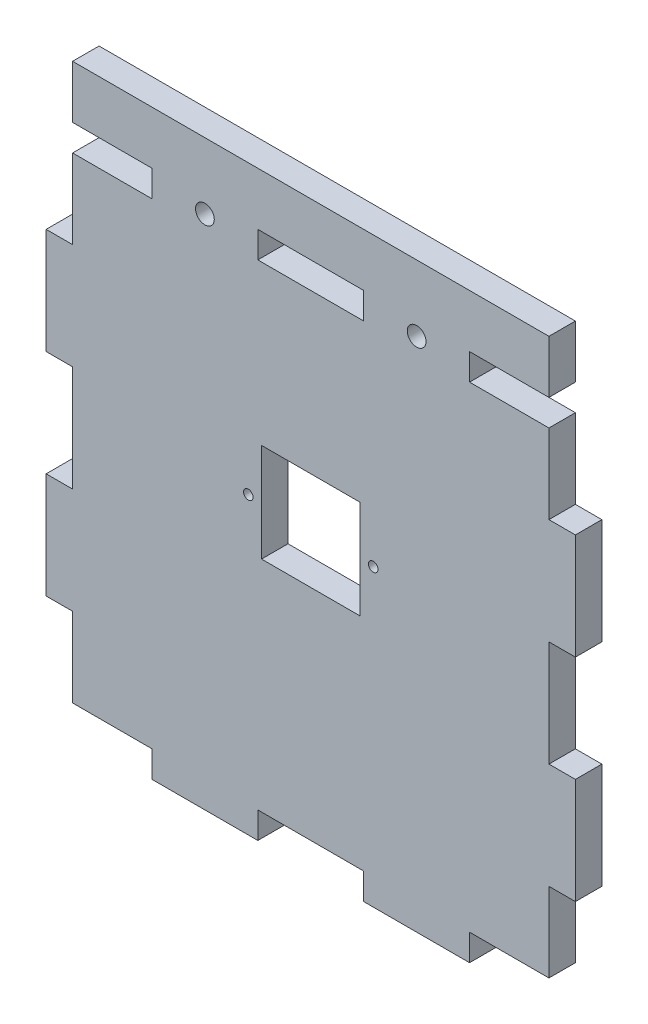
SolidWorks part; units mm, degrees
ref_plane "Front Plane" through (0, 0, 0) normal (0, 0, 1) x (1, 0, 0)
ref_plane "Top Plane" through (0, 0, 0) normal (0, 1, 0) x (1, 0, 0)
ref_plane "Right Plane" through (0, 0, 0) normal (1, 0, 0) x (0, 0, -1)
sketch "Sketch1" plane through (0, 0, 0) normal (0, 0, 1) x (1, 0, 0)
  line L1 (0, 0) -> (127, 0)
  line L2 (0, 0) -> (0, 139.7)
  line L3 (0, 139.7) -> (127, 139.7)
  line L4 (127, 0) -> (127, 139.7)
  dimension "D1" = 127
  dimension "D2" = 139.7
extrude "Boss-Extrude1" add sketch "Sketch1" along normal blind 6.35
sketch "Sketch5" plane through (0, 0, 6.35) normal (0, 0, 1) x (1, 0, 0)
  line L1 (0, 0) -> (6.35, 0)
  line L2 (0, 0) -> (0, 25.4)
  line L3 (0, 25.4) -> (6.35, 25.4)
  line L4 (6.35, 0) -> (6.35, 25.4)
  dimension "D1" = 25.4
  dimension "D2" = 6.35
extrude "Cut-Extrude4" cut sketch "Sketch5" against normal blind 6.35
sketch "Sketch6" plane through (0, 0, 6.35) normal (0, 0, 1) x (1, 0, 0)
  line L1 (0, 0) -> (25.4, 0)
  line L2 (0, 0) -> (0, 6.35)
  line L3 (0, 6.35) -> (25.4, 6.35)
  line L4 (25.4, 0) -> (25.4, 6.35)
  dimension "D1" = 6.35
  dimension "D2" = 25.4
extrude "Cut-Extrude5" cut sketch "Sketch6" against normal blind 6.35
pattern_linear "LPattern5" count 3 spacing 50.8 along (0, 1, 0) count 2 spacing 120.65 along (1, 0, 0) of "Cut-Extrude4"
pattern_linear "LPattern6" count 3 spacing 50.8 along (1, 0, 0) count 2 spacing 120.65 along (0, 1, 0) of "Cut-Extrude5"
sketch "Sketch7" plane through (0, 0, 6.35) normal (0, 0, 1) x (1, 0, 0)
  line L1 (6.35, 120.65) -> (0, 120.65)
  line L2 (6.35, 120.65) -> (6.35, 139.7)
  line L3 (6.35, 139.7) -> (0, 139.7)
  line L4 (0, 120.65) -> (0, 139.7)
  dimension "D1" = 6.35
  dimension "D2" = 19.05
extrude "Cut-Extrude6" cut sketch "Sketch7" against normal blind 6.35
sketch "Sketch12" plane through (0, 0, 6.35) normal (0, 0, 1) x (1, 0, 0)
  line L0 (127, 127) -> (127, 139.7) construction
  line L1 (127, 139.7) -> (120.65, 139.7)
  line L2 (127, 139.7) -> (127, 127)
  line L3 (127, 127) -> (120.65, 127)
  line L4 (120.65, 139.7) -> (120.65, 127)
  line L5 (127, 139.7) -> (6.35, 139.7) construction
  dimension "D1" = 6.35
  dimension "D2" = 12.7
extrude "Cut-Extrude9" cut sketch "Sketch12" against normal blind 7.62
hole_wizard "#8 Clearance Hole1" positions "Sketch10" profile "Sketch9" hole size "#8" standard "ANSI Inch"
sketch "Sketch10" plane through (0, 0, 6.35) normal (0, 0, 1) x (1, 0, 0)
  line L2 (25.4, 120.65) -> (25.4, 127) construction
  line L3 (76.2, 127) -> (50.8, 127) construction
  point P0 (38.1, 123.825)
  point P2 (88.9, 123.825)
  point P10 (25.4, 123.825)
  dimension "D1" = 12.7
  dimension "D3" = 12.7
  dimension "D4" = 3.175
sketch "Sketch9" plane through (38.1, 123.825, 6.35) normal (1, 0, 0) x (0, -1, 0)
  line L0 (0, 0) -> (0, 11.5107)
  line L1 (0, 11.5107) -> (2.2479, 10.16)
  line L2 (2.2479, 10.16) -> (2.2479, 0)
  line L5 (2.2479, 0) -> (0, 0)
  line L10 (0, 11.5107) -> (-2.2479, 10.16) construction
  line L11 (0, -6.35) -> (0, 107.95) construction
  dimension "Hole Dia." = 4.4958
  dimension "Hole Depth" = 10.16
  dimension "Drill Angle" = 118
sketch "Sketch11" plane through (0, 0, 6.35) normal (0, 0, 1) x (1, 0, 0)
  line L1 (51.689, 82.55) -> (75.311, 82.55)
  line L2 (51.689, 82.55) -> (51.689, 58.928)
  line L3 (51.689, 58.928) -> (75.311, 58.928)
  line L4 (75.311, 82.55) -> (75.311, 58.928)
  line L6 (0, 101.6) -> (0, 76.2) construction
  line L7 (50.8, 120.65) -> (76.2, 120.65) construction
  circle A0 centre (48.514, 70.739) radius 1.143
  circle A1 centre (78.486, 70.739) radius 1.143
  point P6 (63.5, 82.55)
  point P13 (75.311, 70.739)
  point P14 (51.689, 70.739)
  dimension "D5" = 2.286
  dimension "D6" = 2.286
  dimension "D7" = 14.986
  dimension "D8" = 14.986
  dimension "D1" = 38.1
  dimension "D2" = 23.622
  dimension "D3" = 23.622
  dimension "D4" = 63.5
extrude "Cut-Extrude8" cut sketch "Sketch11" against normal blind 7.62
